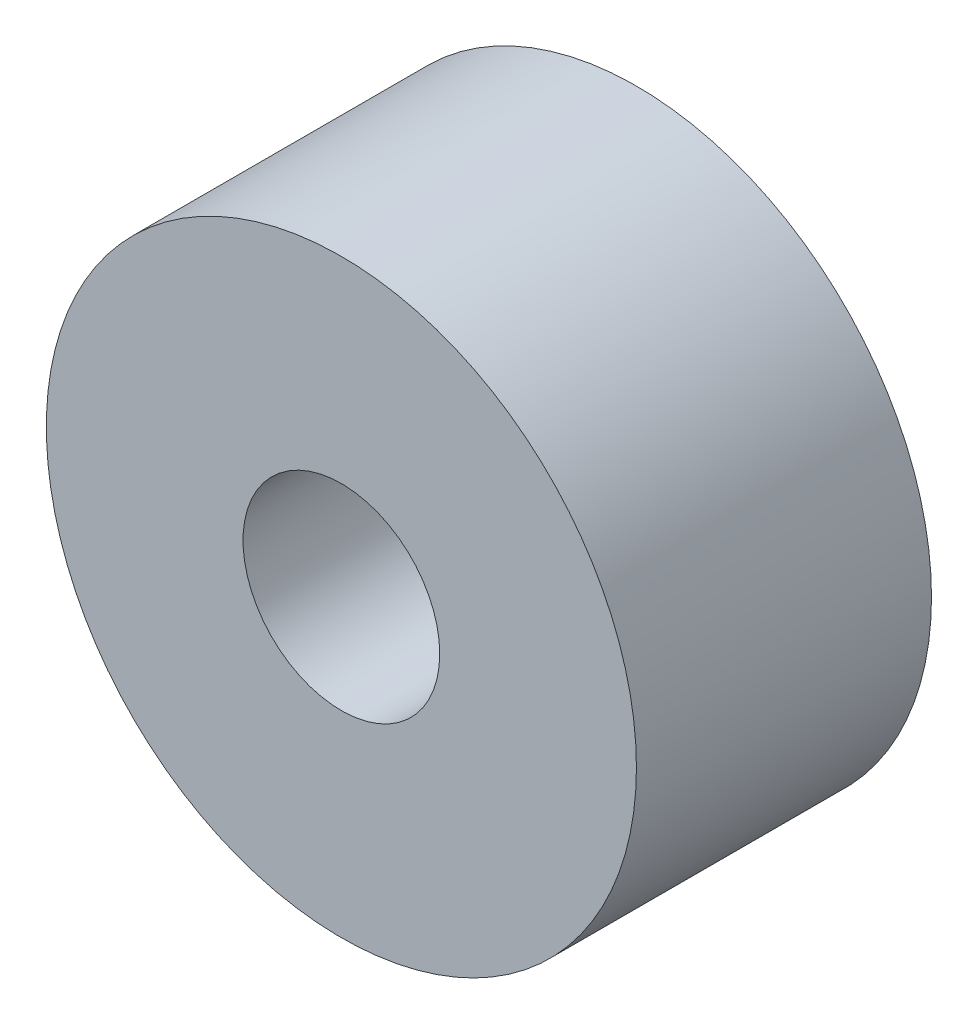
SolidWorks part; units mm, degrees
material "Custom Plastic"
ref_plane "X-Y Datum" through (0, 0, 0) normal (0, 0, 1) x (1, 0, 0)
ref_plane "X-Z Datum" through (0, 0, 0) normal (0, 1, 0) x (1, 0, 0)
ref_plane "Y-Z Datum" through (0, 0, 0) normal (1, 0, 0) x (0, 0, -1)
sketch "Sketch1" plane through (0, 0, 0) normal (0, 0, 1) x (1, 0, 0)
  circle A0 centre (0, 0) radius 1
  circle A1 centre (0, 0) radius 3
  dimension "D1" = 2
  dimension "D2" = 6
extrude "Boss-Extrude1" add sketch "Sketch1" along normal blind 3
